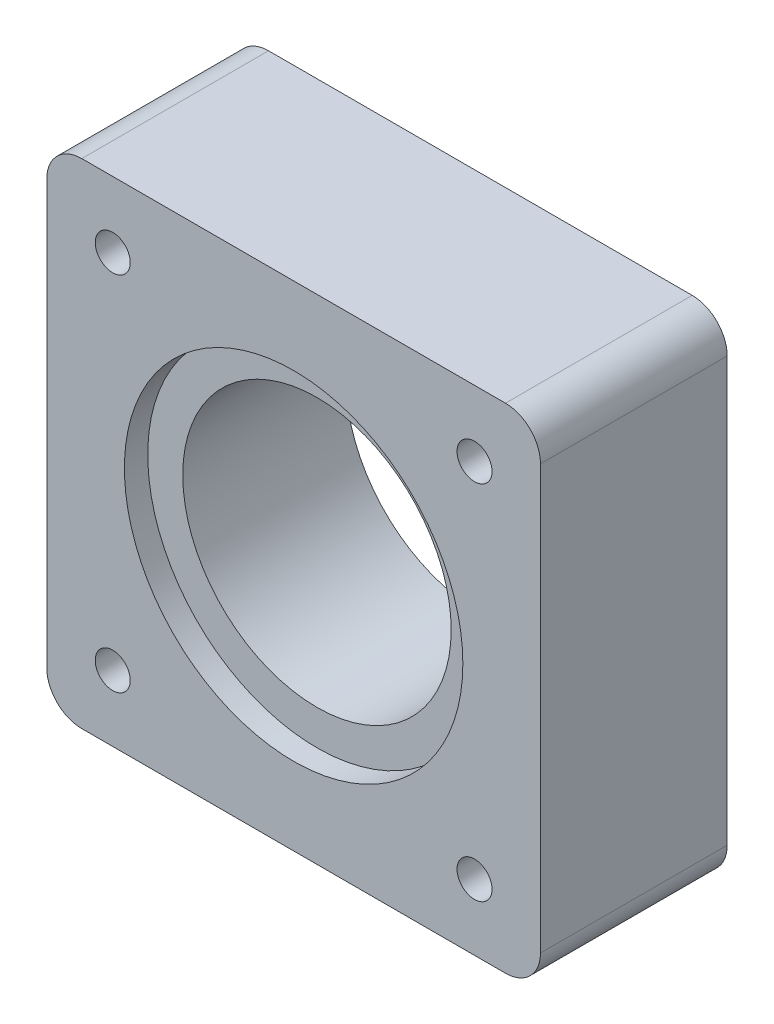
SolidWorks part; units mm, degrees
ref_plane "Plan de face" through (0, 0, 0) normal (0, 0, 1) x (1, 0, 0)
ref_plane "Plan de dessus" through (0, 0, 0) normal (0, 1, 0) x (1, 0, 0)
ref_plane "Plan de droite" through (0, 0, 0) normal (1, 0, 0) x (0, 0, -1)
sketch "Esquisse1" plane through (0, 0, 0) normal (0, 0, 1) x (1, 0, 0)
  line L1 (0, 0) -> (42.3, 0)
  line L2 (0, 0) -> (0, 42.3)
  line L3 (0, 42.3) -> (42.3, 42.3)
  line L4 (42.3, 0) -> (42.3, 42.3)
  dimension "D1" = 42.3
  dimension "D2" = 42.3
extrude "Boss.-Extru.1" add sketch "Esquisse1" along normal blind 16
sketch "Esquisse2" plane through (0, 0, 0) normal (0, 0, 1) x (1, 0, 0)
  line L0 (42.3, 0) -> (42.3, 42.3) construction
  line L2 (42.3, 42.3) -> (0, 42.3) construction
  line L3 (0, 42.3) -> (0, 0) construction
  line L5 (0, 0) -> (42.3, 0) construction
  circle A0 centre (36.65, 36.65) radius 1.5
  circle A1 centre (5.65, 36.65) radius 1.5
  circle A2 centre (5.65, 5.65) radius 1.5
  circle A3 centre (36.65, 5.65) radius 1.5
  dimension "D1" = 3
  dimension "D2" = 3
  dimension "D3" = 3
  dimension "D4" = 3
  dimension "D9" = 5.65
  dimension "D5" = 5.65
  dimension "D6" = 5.65
  dimension "D7" = 5.65
  dimension "D8" = 5.65
  dimension "D10" = 5.65
  dimension "D11" = 5.65
  dimension "D12" = 5.65
extrude "Enlèv. mat.-Extru.2" cut sketch "Esquisse2" along normal through all
fillet "Congé1" radius 3 2 edges at (0, 42.3, 8) (42.3, 42.3, 8)
fillet "Congé2" radius 3 2 edges at (42.3, 0, 8) (0, 0, 8)
sketch "Esquisse4" plane through (0, 0, 0) normal (0, 0, 1) x (1, 0, 0)
  line L0 (39.3, 42.3) -> (3, 42.3) construction
  line L1 (0, 39.3) -> (0, 3) construction
  circle A0 centre (21.15, 21.15) radius 11.5
  point P6 (21.15, 42.3)
  dimension "D1" = 23
  dimension "D2" = 21.15
  dimension "D3" = 21.15
extrude "Enlèv. mat.-Extru.4" cut sketch "Esquisse4" along normal through all
sketch "Esquisse5" plane through (0, 0, 0) normal (0, 0, 1) x (1, 0, 0)
  circle A0 centre (36.65, 36.65) radius 2.85
  circle A1 centre (5.65, 36.65) radius 2.85
  circle A2 centre (5.65, 5.65) radius 2.85
  circle A3 centre (36.65, 5.65) radius 2.85
  dimension "D1" = 5.7
  dimension "D2" = 5.7
  dimension "D3" = 5.7
  dimension "D4" = 5.7
extrude "Enlèv. mat.-Extru.5" cut sketch "Esquisse5" along normal blind 10
sketch "Esquisse6" plane through (0, 0, 0) normal (0, 0, 1) x (1, 0, 0)
  line L0 (3, 0) -> (39.3, 0) construction
  line L1 (0, 39.3) -> (0, 3) construction
  line L2 (42.3, 3) -> (42.3, 39.3) construction
  circle A0 centre (29.3, 6.5) radius 4.25
  circle A1 centre (13, 6.5) radius 4.25
  dimension "D1" = 8.5
  dimension "D2" = 8.5
  dimension "D4" = 6.5
  dimension "D5" = 13
  dimension "D6" = 13
  dimension "D3" = 6.5
extrude "Enlèv. mat.-Extru.6" cut sketch "Esquisse6" along normal blind 12
sketch "Esquisse7" plane through (0, 0, 16) normal (0, 0, 1) x (1, 0, 0)
  circle A0 centre (21.15, 21.15) radius 14.5
  circle A1 centre (21.15, 21.15) radius 11.5 construction
  dimension "D1" = 0
  dimension "D2" = 29
extrude "Enlèv. mat.-Extru.7" cut sketch "Esquisse7" against normal blind 2
